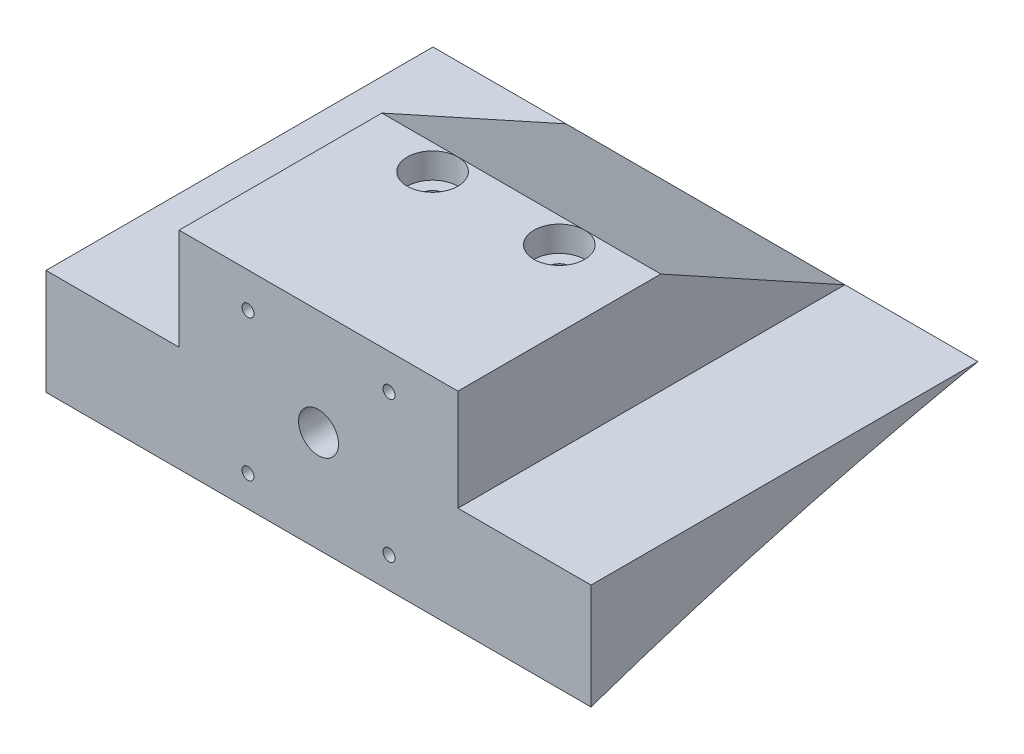
SolidWorks part; units mm, degrees
material "ABS"
ref_plane "Front Plane" through (0, 0, 0) normal (0, 0, 1) x (1, 0, 0)
ref_plane "Top Plane" through (0, 0, 0) normal (0, 1, 0) x (1, 0, 0)
ref_plane "Right Plane" through (0, 0, 0) normal (1, 0, 0) x (0, 0, -1)
curve "Curve1"
  spline degree 3 poles (0, 0.0012, 1.0003) (0, 0.0015, 0.9994) (0, 0.0028, 0.9958) (0, 0.0055, 0.9879) (0, 0.0099, 0.9747) (0, 0.0159, 0.9565) (0, 0.0233, 0.9333) (0, 0.0318, 0.9054) (0, 0.0411, 0.8731) (0, 0.051, 0.8366) (0, 0.0612, 0.7964) (0, 0.0713, 0.7528) (0, 0.0811, 0.7063) (0, 0.0903, 0.6574) (0, 0.0985, 0.6067) (0, 0.1057, 0.5546) (0, 0.1115, 0.5018) (0, 0.1158, 0.4488) (0, 0.1186, 0.3959) (0, 0.1189, 0.3436) (0, 0.1164, 0.2927) (0, 0.1112, 0.2442) (0, 0.1037, 0.1988) (0, 0.0942, 0.157) (0, 0.0831, 0.1194) (0, 0.0711, 0.0865) (0, 0.0584, 0.0585) (0, 0.0457, 0.0357) (0, 0.0334, 0.0184) (0, 0.0218, 0.0064) (0, 0.0108, -0.0005) (0, -0.0003, -0.0011) (0, -0.0092, 0.0055) (0, -0.0148, 0.017) (0, -0.0185, 0.0329) (0, -0.0204, 0.0533) (0, -0.0208, 0.0781) (0, -0.0198, 0.107) (0, -0.0176, 0.1398) (0, -0.0147, 0.176) (0, -0.0111, 0.2153) (0, -0.0074, 0.2574) (0, -0.0037, 0.3019) (0, -0.0005, 0.3484) (0, 0.002, 0.397) (0, 0.0037, 0.4471) (0, 0.0055, 0.4983) (0, 0.0069, 0.5496) (0, 0.0079, 0.6006) (0, 0.0085, 0.6505) (0, 0.0086, 0.699) (0, 0.0083, 0.7455) (0, 0.0076, 0.7894) (0, 0.0065, 0.8302) (0, 0.0053, 0.8675) (0, 0.0039, 0.9007) (0, 0.0027, 0.9296) (0, 0.0013, 0.9539) (0, 0.0006, 0.9727) (0, -0.0011, 0.9872) (0, 0, 0.9944) (0, -0.002, 0.9999) (0, -0.0005, 1) (0, 0, 1) knots 0 0 0 0 0.001372 0.005465 0.012235 0.021602 0.033461 0.047671 0.064081 0.082496 0.102719 0.124527 0.147676 0.171913 0.196978 0.222597 0.248497 0.274385 0.300041 0.32569 0.350525 0.37428 0.396711 0.417577 0.436654 0.453744 0.46868 0.481329 0.491631 0.499616 0.505546 0.510185 0.514824 0.520702 0.528516 0.538466 0.550543 0.564643 0.580638 0.598345 0.617584 0.638174 0.659922 0.682632 0.706121 0.730727 0.7557 0.780732 0.805564 0.829932 0.85357 0.876213 0.89761 0.917519 0.935698 0.951943 0.966047 0.97784 0.987174 0.993932 0.998018 0.999386 1 1 1 1
sketch "Sketch1" plane through (0, 0, 0) normal (1, 0, 0) x (0, 0, -1)
  line L3 (195.725, 0) -> (-195.725, 0) construction
  line L4 (-258.7498, 26.4626) -> (-355.6872, 26.4626)
  line L5 (-355.6872, 26.4626) -> (-355.6872, 0)
  spline S1 degree 3 poles (-355.6872, 0) (-355.3706, 0.108) (-354.109, 0.5382) (-351.285, 1.5029) (-346.6023, 3.0589) (-336.8154, 6.2519) (-320.4299, 11.2778) (-301.3571, 16.5496) (-283.1673, 21.0862) (-270.1079, 24.0716) (-261.8289, 25.8283) (-258.7498, 26.4626) knots 0 0 0 0 0.001372 0.005465 0.012235 0.021602 0.047671 0.082496 0.102719 0.124527 0.137416 0.137416 0.137416 0.137416
  dimension "D1" = 26.4626
  dimension "D2" = 355.6872
  dimension "D3" = 96.9374
extrude "Boss-Extrude1" add sketch "Sketch1" along normal mid plane 136.525
sketch "Sketch4" plane through (0, 0, 355.6872) normal (0, 0, 1) x (1, 0, 0)
  line L0 (68.2625, 26.4626) -> (-68.2625, 26.4626) construction
  line L1 (-34.925, 51.8626) -> (34.925, 51.8626)
  line L2 (-34.925, 51.8626) -> (-34.925, 26.4626)
  line L3 (-34.925, 26.4626) -> (34.925, 26.4626)
  line L4 (34.925, 51.8626) -> (34.925, 26.4626)
  point P6 (0, 26.4626)
  dimension "D1" = 25.4
  dimension "D2" = 69.85
extrude "Boss-Extrude2" add sketch "Sketch4" against normal blind 50.8
sketch "Sketch2" plane through (0, 26.4626, 0) normal (0, 1, 0) x (1, 0, 0)
  line L0 (-68.2625, -311.2372) -> (68.2625, -311.2372) construction
  line L1 (-68.2625, -258.7498) -> (-68.2625, -355.6872) construction
  line L2 (68.2625, -258.7498) -> (68.2625, -355.6872) construction
  line L3 (-15.875, -311.2372) -> (-15.875, -258.7498) construction
  line L4 (68.2625, -258.7498) -> (-68.2625, -258.7498) construction
  line L5 (15.875, -311.2372) -> (15.875, -258.7498) construction
  line L6 (-68.2625, -286.8403) -> (-15.875, -286.8403) construction
  line L7 (-15.875, -286.8403) -> (15.875, -286.8403) construction
  line L8 (15.875, -286.8403) -> (68.2625, -286.8403) construction
  line L9 (-34.925, -355.6872) -> (-68.2625, -355.6872) construction
  circle A0 centre (-15.875, -311.2372) radius 3.175
  circle A1 centre (15.875, -311.2372) radius 3.175
  dimension "D1" = 6.35
  dimension "D2" = 6.35
  dimension "D3" = 31.75
  dimension "D4" = 44.45
extrude "Cut-Extrude1" cut sketch "Sketch2" against normal through all and the other way through all
sketch "Sketch5" plane through (0, 0, 355.6872) normal (0, 0, 1) x (1, 0, 0)
  line L0 (68.2625, 0) -> (-68.2625, 0) construction
  circle A0 centre (0, 25.4) radius 5
  dimension "D1" = 10
  dimension "D2" = 25.4
extrude "Cut-Extrude2" cut sketch "Sketch5" against normal blind 12.7
sketch "Sketch6" plane through (0, 0, 355.6872) normal (0, 0, 1) x (1, 0, 0)
  line L0 (0, 25.4) -> (27.6134, 53.0134) construction
  line L1 (0, 25.4) -> (45.1172, 25.4) construction
  circle A0 centre (17.6777, 43.0777) radius 1.5
  dimension "D1" = 3
  dimension "D2" = 25
  dimension "D3" = 45
extrude "Cut-Extrude3" cut sketch "Sketch6" against normal blind 6.35
pattern_circular "CirPattern1" count 4 over 360 about axis through (0, 25.4, 0) along (0, 0, 1) of "Cut-Extrude3"
sketch "Sketch7" plane through (-34.925, 0, 0) normal (-1, 0, 0) x (0, 0, 1)
  line L0 (304.8872, 51.8626) -> (258.7498, 26.4626)
  line L1 (258.7498, 26.4626) -> (355.6872, 26.4626) construction
  line L2 (258.7498, 26.4626) -> (304.8872, 26.4626)
  line L3 (304.8872, 26.4626) -> (304.8872, 51.8626)
  spline S0 degree 3 poles (355.6872, 0) (355.3706, 0.108) (354.109, 0.5382) (351.285, 1.5029) (346.6023, 3.0589) (336.8154, 6.2519) (320.4299, 11.2778) (301.3571, 16.5496) (283.1673, 21.0862) (270.1079, 24.0716) (261.8289, 25.8283) (258.7498, 26.4626) knots 0 0 0 0 0.001372 0.005465 0.012235 0.021602 0.047671 0.082496 0.102719 0.124527 0.137416 0.137416 0.137416 0.137416 construction
extrude "Boss-Extrude3" add sketch "Sketch7" against normal up to surface (69.85 mm away) up to face at (34.925, 39.1626, 330.2872)
sketch "Sketch8" plane through (0, 51.8626, 0) normal (0, 1, 0) x (1, 0, 0)
  circle A0 centre (15.875, -311.2372) radius 6.35
  circle A1 centre (-15.875, -311.2372) radius 6.35
  dimension "D1" = 12.7
extrude "Cut-Extrude4" cut sketch "Sketch8" against normal blind 6.35
